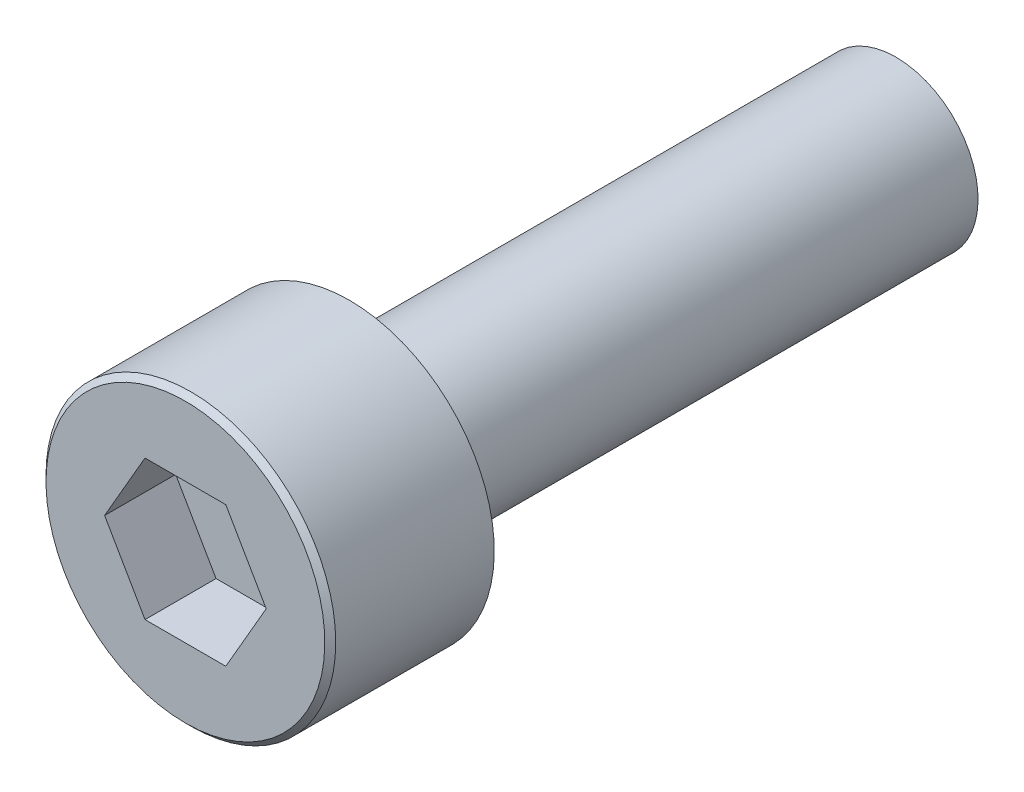
SolidWorks part; units mm, degrees
material "AISI 304"
ref_plane "前视基准面" through (0, 0, 0) normal (0, 0, 1) x (1, 0, 0)
ref_plane "上视基准面" through (0, 0, 0) normal (0, 1, 0) x (1, 0, 0)
ref_plane "右视基准面" through (0, 0, 0) normal (1, 0, 0) x (0, 0, -1)
sketch "草图1" plane through (0, 0, 0) normal (1, 0, 0) x (0, 0, -1)
  line L0 (0, 0) -> (0, 2.65)
  line L1 (0, 2.65) -> (3, 2.65)
  line L2 (3, 2.65) -> (3, 1.5)
  line L3 (3, 1.5) -> (13, 1.5)
  line L4 (13, 1.5) -> (13, 0)
  line L5 (13, 0) -> (0, 0) construction
  line L6 (0, 0) -> (13, 0)
  dimension "D1" = 5.3
  dimension "D2" = 3
  dimension "D3" = 3
  dimension "D4" = 10
revolve "旋转1" add sketch "草图1" angle 360 about L5
cosmetic thread "装饰螺纹线1"
sketch "草图2" plane through (0, 0, 0) normal (0, 0, 1) x (1, 0, 0)
  line L1 (0.739, 1.28) -> (-0.739, 1.28)
  line L2 (-0.739, 1.28) -> (-1.478, 0)
  line L3 (-1.478, 0) -> (-0.739, -1.28)
  line L4 (-0.739, -1.28) -> (0.739, -1.28)
  line L5 (0.739, -1.28) -> (1.478, 0)
  line L6 (1.478, 0) -> (0.739, 1.28)
  circle A0 centre (0, 0) radius 1.28 construction
  dimension "D1" = 2.56
extrude "切除-拉伸1" cut sketch "草图2" against normal blind 1.3
chamfer "装饰倒角" distance 0.1 angle 45 1 edges at (0, 2.65, 0)
